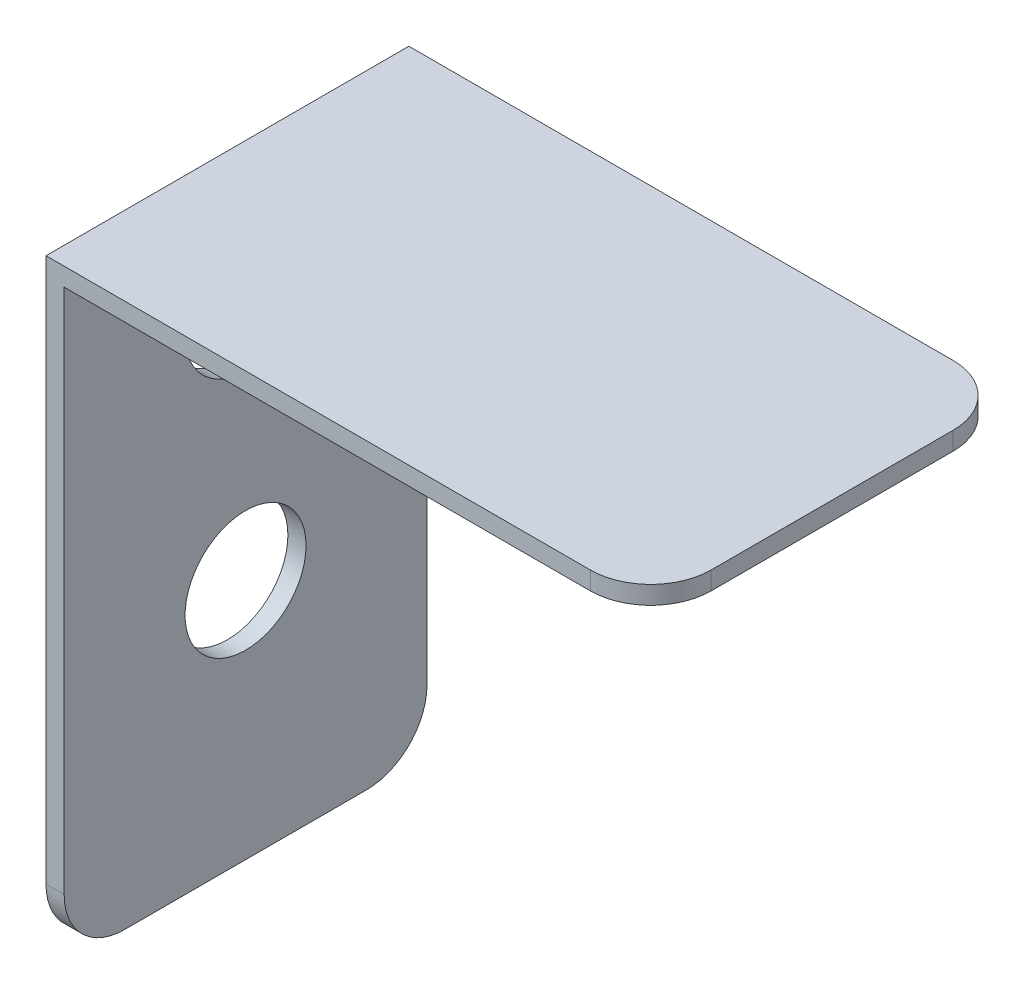
SolidWorks part; units mm, degrees
material "1060 Alloy"
ref_plane "Alzado" through (0, 0, 0) normal (0, 0, 1) x (1, 0, 0)
ref_plane "Planta" through (0, 0, 0) normal (0, 1, 0) x (1, 0, 0)
ref_plane "Vista lateral" through (0, 0, 0) normal (1, 0, 0) x (0, 0, -1)
sketch "Sketch1" plane through (0, 0, 0) normal (0, 0, 1) x (1, 0, 0)
  line L0 (0, 0) -> (0, 100)
  line L1 (0, 100) -> (100, 100)
  line L2 (100, 100) -> (100, 97)
  line L3 (0, 0) -> (3, 0)
  line L4 (3, 0) -> (3, 97)
  line L5 (3, 97) -> (100, 97)
extrude "Boss-Extrude1" add sketch "Sketch1" along normal blind 60
fillet "Fillet1" radius 10 2 edges at (100, 98.5, 0) (100, 98.5, 60)
fillet "Fillet2" radius 10 2 edges at (1.5, 0, 0) (1.5, 0, 60)
sketch "Sketch2" plane through (3, 0, 0) normal (1, 0, 0) x (0, 0, -1)
  circle A0 centre (-30, 40) radius 10
  circle A1 centre (-30, 80) radius 10
extrude "Cut-Extrude1" cut sketch "Sketch2" against normal blind 60
